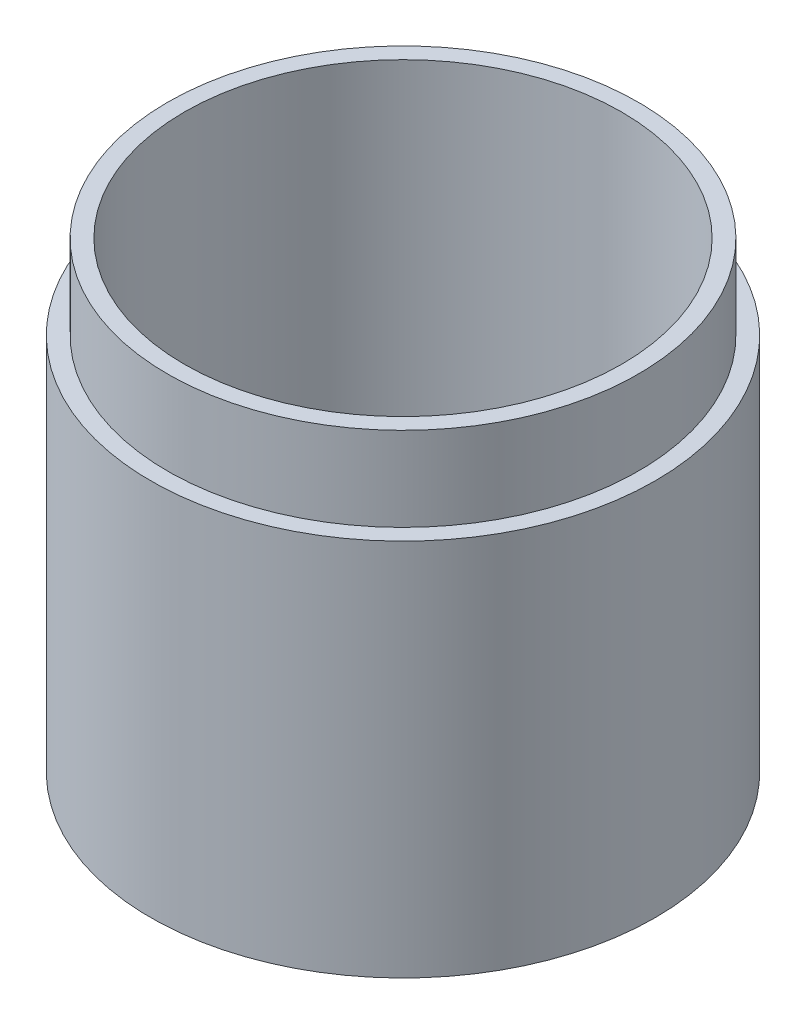
SolidWorks part; units mm, degrees
ref_plane "Front Plane" through (0, 0, 0) normal (0, 0, 1) x (1, 0, 0)
ref_plane "Top Plane" through (0, 0, 0) normal (0, 1, 0) x (1, 0, 0)
ref_plane "Right Plane" through (0, 0, 0) normal (1, 0, 0) x (0, 0, -1)
sketch "Sketch1" plane through (0, 0, 0) normal (0, 0, 1) x (1, 0, 0)
  line L0 (0, 0) -> (38.1, 0)
  line L1 (38.1, 0) -> (38.1, 57.15)
  line L2 (38.1, 57.15) -> (35.56, 57.15)
  line L3 (35.56, 57.15) -> (35.56, 69.85)
  line L4 (35.56, 69.85) -> (33.02, 69.85)
  line L5 (33.02, 69.85) -> (33.02, 5.08)
  line L6 (33.02, 5.08) -> (0, 5.08)
  line L7 (0, 5.08) -> (0, 0)
  dimension "D1" = 2.54
  dimension "D2" = 5.08
  dimension "D3" = 5.08
  dimension "D4" = 69.85
  dimension "D5" = 12.7
  dimension "D6" = 38.1
revolve "Revolve1" add sketch "Sketch1" angle 360 about L7
